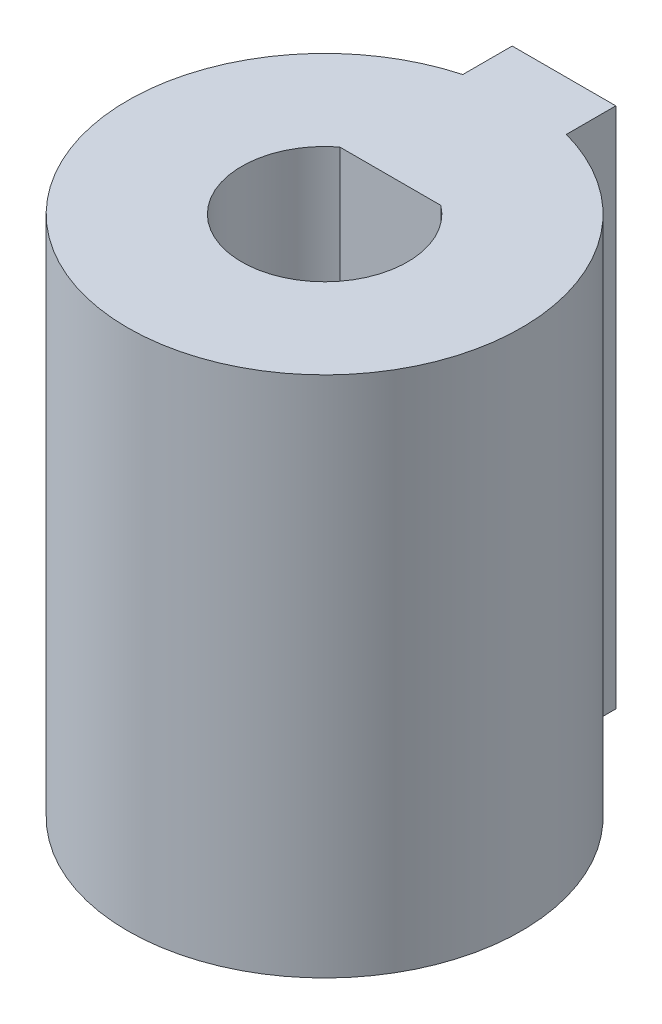
SolidWorks part; units mm, degrees
material "NYLON (PA)"
ref_plane "Alzado" through (0, 0, 0) normal (0, 0, 1) x (1, 0, 0)
ref_plane "Planta" through (0, 0, 0) normal (0, 1, 0) x (1, 0, 0)
ref_plane "Vista lateral" through (0, 0, 0) normal (1, 0, 0) x (0, 0, -1)
sketch "Croquis1" plane through (0, 0, 0) normal (0, 1, 0) x (1, 0, 0)
  line L0 (-2.4395, 3.17) -> (2.4395, 3.17)
  line L1 (0, 0) -> (0, -4) construction
  line L2 (0, 14.05) -> (0, 0) construction
  line L3 (-2.5, 11.55) -> (2.5, 11.55)
  line L4 (-2.5, 11.55) -> (-2.5, 9.1652)
  line L5 (-2.5, 9.1652) -> (0, 9.1652) construction
  line L6 (2.5, 11.55) -> (2.5, 9.1652)
  line L7 (0, 9.1652) -> (2.5, 9.1652) construction
  arc A0 (-2.4395, 3.17) -> (2.4395, 3.17) centre (0, 0) ccw
  arc A1 (-2.5, 9.1652) -> (2.5, 9.1652) centre (0, 0) ccw
  arc A2 (2.4395, 3.17) -> (-2.4395, 3.17) centre (0, 0) ccw construction
  circle A3 centre (0, 0) radius 14.05 construction
  arc A4 (2.5, 9.1652) -> (0, 9.5) centre (0, 0) ccw construction
  arc A5 (0, 9.5) -> (-2.5, 9.1652) centre (0, 0) ccw construction
  point P10 (0, 11.55)
  dimension "D1" = 19
  dimension "D2" = 8
  dimension "D4" = 28.1
  dimension "D3" = 7.17
  dimension "D5" = 2.5
  dimension "D6" = 5
extrude "Saliente-Extruir1" add sketch "Croquis1" along normal blind 25.2
